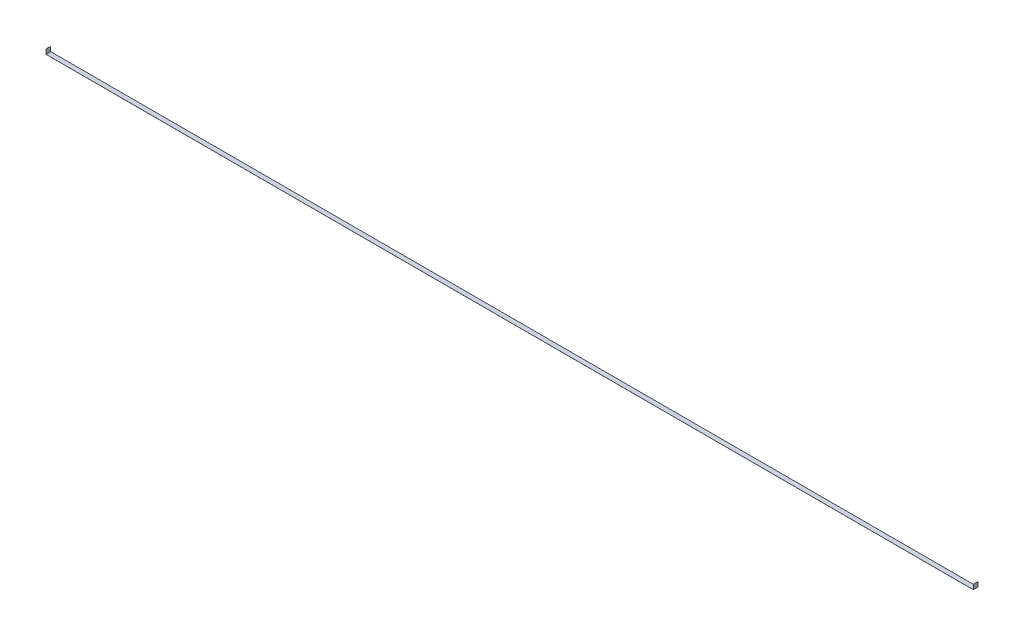
SolidWorks part; units mm, degrees
material "Nylon 101"
ref_plane "Front Plane" through (0, 0, 0) normal (0, 0, 1) x (1, 0, 0)
ref_plane "Top Plane" through (0, 0, 0) normal (0, 1, 0) x (1, 0, 0)
ref_plane "Right Plane" through (0, 0, 0) normal (1, 0, 0) x (0, 0, -1)
sketch "Sketch1" plane through (0, 0, 0) normal (0, 0, 1) x (1, 0, 0)
  line L0 (-2527.3, 0) -> (2527.3, 0)
  line L1 (2527.3, 0) -> (2527.3, 25.4)
  line L2 (-2527.3, 0) -> (-2527.3, 25.4)
  point P4 (0, 0)
  dimension "D1" = 25.4
  dimension "D2" = 5054.6
extrude "Extrude-Thin1" add sketch "Sketch1" along normal blind 25.4 thin
